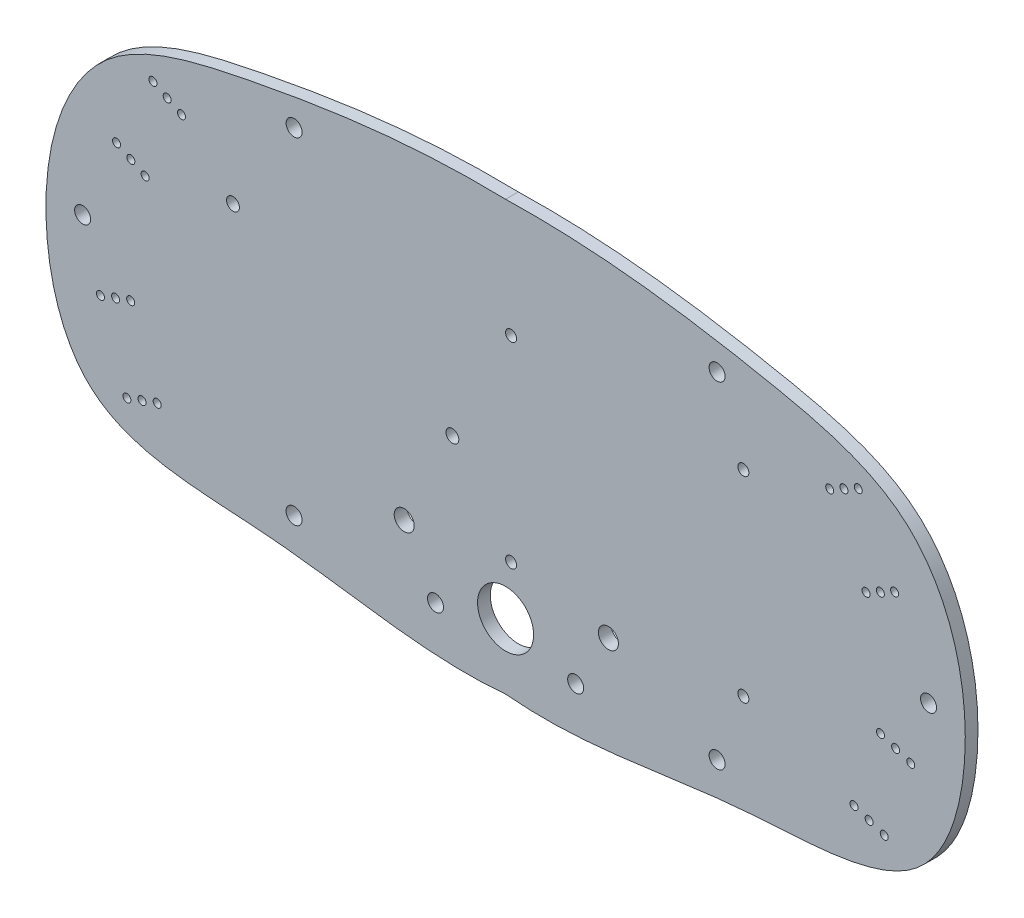
SolidWorks part; units mm, degrees
material "Acrylic (Medium-high impact)"
ref_plane "Front Plane" through (0, 0, 0) normal (0, 0, 1) x (1, 0, 0)
ref_plane "Top Plane" through (0, 0, 0) normal (0, 1, 0) x (1, 0, 0)
ref_plane "Right Plane" through (0, 0, 0) normal (1, 0, 0) x (0, 0, -1)
sketch "Sketch2" plane through (0, 0, 0) normal (0, 0, 1) x (1, 0, 0)
  circle A10 centre (105.6294, 50.8755) radius 2
  circle A11 centre (97.4088, 36.971) radius 1
  circle A12 centre (90.7902, 18.0979) radius 1
  circle A13 centre (90.0252, 67.0441) radius 1
  circle A14 centre (80.9467, 84.8649) radius 1
  circle A15 centre (52.8245, 12.2328) radius 2
  circle A16 centre (17.5, 11) radius 2
  circle A24 centre (-17.5, 11) radius 2
  circle A25 centre (-52.8245, 12.2328) radius 2
  circle A30 centre (-105.6294, 50.8755) radius 2
  circle A31 centre (93.6342, 38.2948) radius 1
  circle A32 centre (87.0156, 19.4217) radius 1
  circle A37 centre (84.5108, 86.6806) radius 1
  circle A38 centre (93.5894, 68.8598) radius 1
  circle A39 centre (88.075, 88.4963) radius 1
  circle A40 centre (97.1535, 70.6755) radius 1
  circle A41 centre (101.1834, 35.6473) radius 1
  circle A42 centre (94.5649, 16.7742) radius 1
  circle A43 centre (52.8245, 96.0993) radius 2
  circle A44 centre (-52.8245, 96.0993) radius 2
  circle A45 centre (-90.0252, 67.0441) radius 1
  circle A46 centre (-93.5894, 68.8598) radius 1
  circle A47 centre (-97.1535, 70.6755) radius 1
  circle A48 centre (-88.075, 88.4963) radius 1
  circle A49 centre (-84.5108, 86.6806) radius 1
  circle A50 centre (-80.9467, 84.8649) radius 1
  circle A51 centre (-101.1834, 35.6473) radius 1
  circle A52 centre (-97.4088, 36.971) radius 1
  circle A53 centre (-93.6342, 38.2948) radius 1
  circle A54 centre (-94.5649, 16.7742) radius 1
  circle A55 centre (-90.7902, 18.0979) radius 1
  circle A56 centre (-87.0156, 19.4217) radius 1
  spline S0 degree 3 poles (0, 0) (-20.953, -1.9173) (-52.0654, 6.5599) (-106.0768, 5.0272) (-118.9056, 49.2019) (-106.9965, 91.1309) (-54.7921, 103.3923) (-22.6856, 107.5733) (0, 107.0408) knots 0 0 0 0 0.21242 0.369252 0.478798 0.640374 0.766906 1 1 1 1
  spline S1 degree 3 poles (0, 0) (20.953, -1.9173) (52.0654, 6.5599) (106.0768, 5.0272) (118.9056, 49.2019) (106.9965, 91.1309) (54.7921, 103.3923) (22.6856, 107.5733) (0, 107.0408) knots 0 0 0 0 0.21242 0.369252 0.478798 0.640374 0.766906 1 1 1 1
  dimension "D1" = 4
  dimension "D2" = 2
  dimension "D3" = 2
  dimension "D4" = 2
  dimension "D5" = 2
  dimension "D8" = 4
  dimension "D9" = 4
  dimension "D14" = 2
  dimension "D15" = 2
  dimension "D16" = 11
  dimension "D13" = 4
  dimension "D6" = 20
  dimension "D7" = 20
  dimension "D10" = 17.5
  dimension "D11" = 4
  dimension "D12" = 4
  dimension "D17" = 11
extrude "Boss-Extrude1" add sketch "Sketch2" along normal blind 3.175
sketch "Sketch3" plane through (0, 0, 3.175) normal (0, 0, 1) x (1, 0, 0)
  circle A0 centre (25.6788, 24.9838) radius 2.5
  circle A1 centre (-25.3212, 24.9838) radius 2.5
  dimension "D1" = 5
extrude "Cut-Extrude1" cut sketch "Sketch3" against normal through all
sketch "Sketch6" plane through (0, 0, 3.175) normal (0, 0, 1) x (1, 0, 0)
  circle A0 centre (-13.2868, 49.2077) radius 1.6
  circle A1 centre (-68.0868, 72.0077) radius 1.6
  dimension "D1" = 3.2
  dimension "D2" = 3.2
  dimension "D3" = 22.8
  dimension "D4" = 54.8
extrude "Cut-Extrude3" cut sketch "Sketch6" against normal through all
sketch "Sketch7" plane through (0, 0, 0) normal (0, 0, -1) x (-1, 0, 0)
  circle A0 centre (0, 16.3061) radius 7
  dimension "D1" = 14
extrude "Cut-Extrude4" cut sketch "Sketch7" against normal blind 10
sketch "Sketch8" plane through (0, 0, 0) normal (0, 0, -1) x (-1, 0, 0)
  circle A0 centre (-59.3765, 29.2418) radius 1.375
  circle A1 centre (-59.3765, 78.2418) radius 1.375
  circle A2 centre (-1.3765, 78.2418) radius 1.375
  circle A3 centre (-1.3765, 29.2418) radius 1.375
  dimension "D1" = 2.75
  dimension "D2" = 2.75
  dimension "D3" = 2.75
  dimension "D4" = 2.75
extrude "Cut-Extrude5" cut sketch "Sketch8" against normal through all
